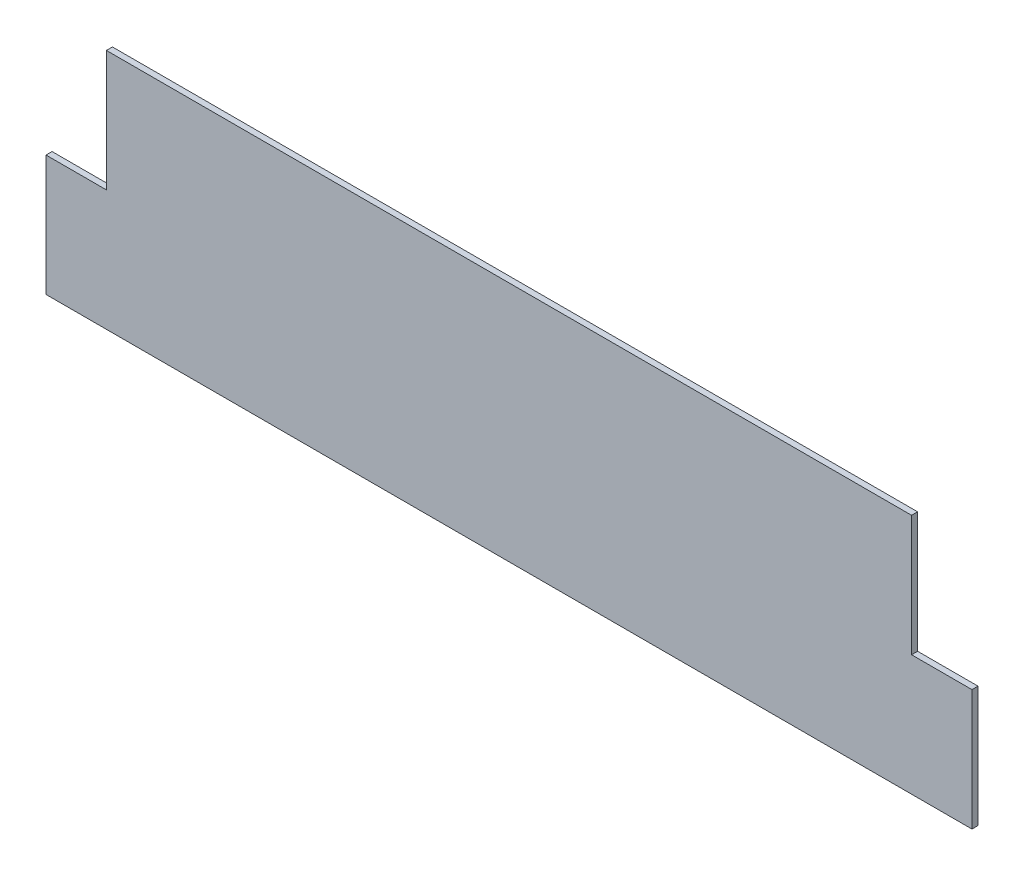
SolidWorks part; units mm, degrees
ref_plane "Přední rovina" through (0, 0, 0) normal (0, 0, 1) x (1, 0, 0)
ref_plane "Horní rovina" through (0, 0, 0) normal (0, 1, 0) x (1, 0, 0)
ref_plane "Pravá rovina" through (0, 0, 0) normal (1, 0, 0) x (0, 0, -1)
sketch "Skica1" plane through (0, 0, 0) normal (0, 0, 1) x (1, 0, 0)
  line L0 (-170.2129, 0) -> (289.7871, 0)
  line L1 (289.7871, 0) -> (289.7871, 60)
  line L2 (289.7871, 60) -> (259.7871, 60)
  line L3 (259.7871, 60) -> (259.7871, 120)
  line L4 (259.7871, 120) -> (-140.2129, 120)
  line L5 (-140.2129, 120) -> (-140.2129, 60)
  line L6 (-140.2129, 60) -> (-170.2129, 60)
  line L7 (-170.2129, 60) -> (-170.2129, 0)
  dimension "D1" = 460
  dimension "D2" = 120
  dimension "D3" = 30
  dimension "D4" = 60
extrude "Přidat vysunutím1" add sketch "Skica1" along normal blind 3
